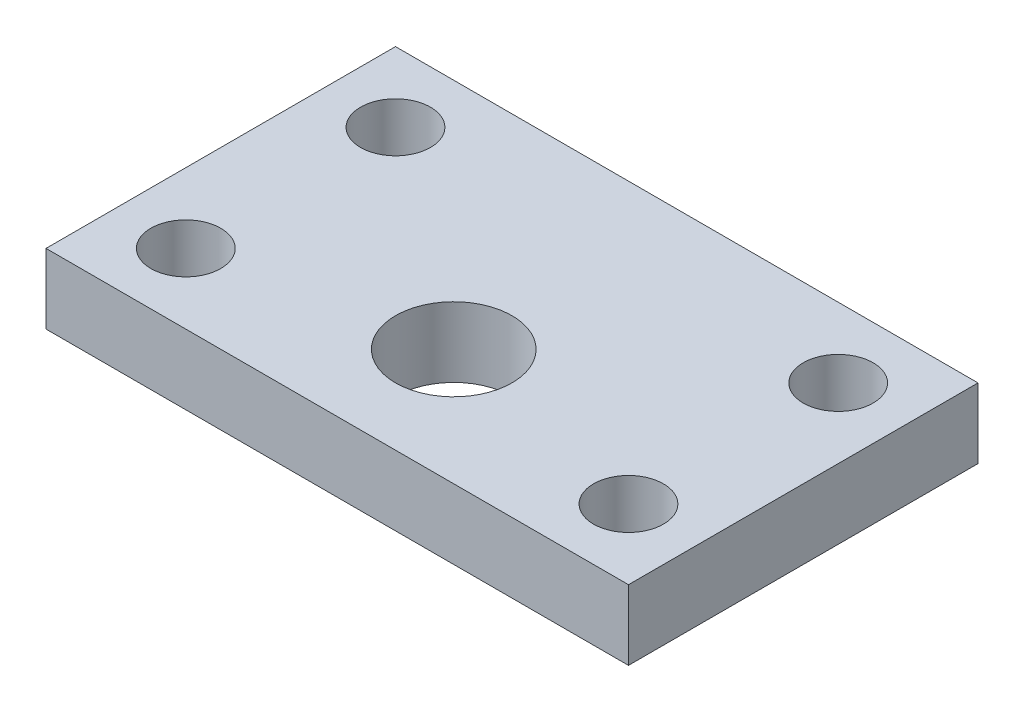
SolidWorks part; units mm, degrees
ref_plane "Front Plane" through (0, 0, 0) normal (0, 0, 1) x (1, 0, 0)
ref_plane "Top Plane" through (0, 0, 0) normal (0, 1, 0) x (1, 0, 0)
ref_plane "Right Plane" through (0, 0, 0) normal (1, 0, 0) x (0, 0, -1)
sketch "Sketch3" plane through (0, 0, 0) normal (0, 1, 0) x (1, 0, 0)
  line L1 (-125, 75) -> (125, 75)
  line L2 (-125, 75) -> (-125, -75)
  line L3 (-125, -75) -> (125, -75)
  line L4 (125, 75) -> (125, -75)
  line L5 (-125, 75) -> (125, -75) construction
  line L6 (-125, -75) -> (125, 75) construction
  point P0 (0, 0)
  dimension "D1" = 250
  dimension "D2" = 150
extrude "Boss-Extrude2" add sketch "Sketch3" along normal mid plane 30
sketch "Sketch5" plane through (0, 15, 0) normal (0, 1, 0) x (1, 0, 0)
  line L2 (-125, -75) -> (125, -75) construction
  circle A1 centre (0, -25) radius 25
  dimension "D1" = 50
  dimension "D2" = 50
extrude "Cut-Extrude1" cut sketch "Sketch5" against normal through all
sketch "Sketch6" plane through (0, 15, 0) normal (0, 1, 0) x (1, 0, 0)
  line L0 (-125, -75) -> (125, -75) construction
  line L1 (-125, 75) -> (-125, -75) construction
  circle A0 centre (-95, -45) radius 15
  circle A1 centre (95, -45) radius 15
  circle A2 centre (95, 45) radius 15
  circle A3 centre (-95, 45) radius 15
  point P4 (0, 0)
  point P6 (-95, 44.2422)
  dimension "D1" = 30
  dimension "D2" = 30
  dimension "D3" = 30
  dimension "D6" = 90
  dimension "D7" = 190
  dimension "D4" = 2
  dimension "D5" = 2
extrude "Cut-Extrude2" cut sketch "Sketch6" against normal through all
